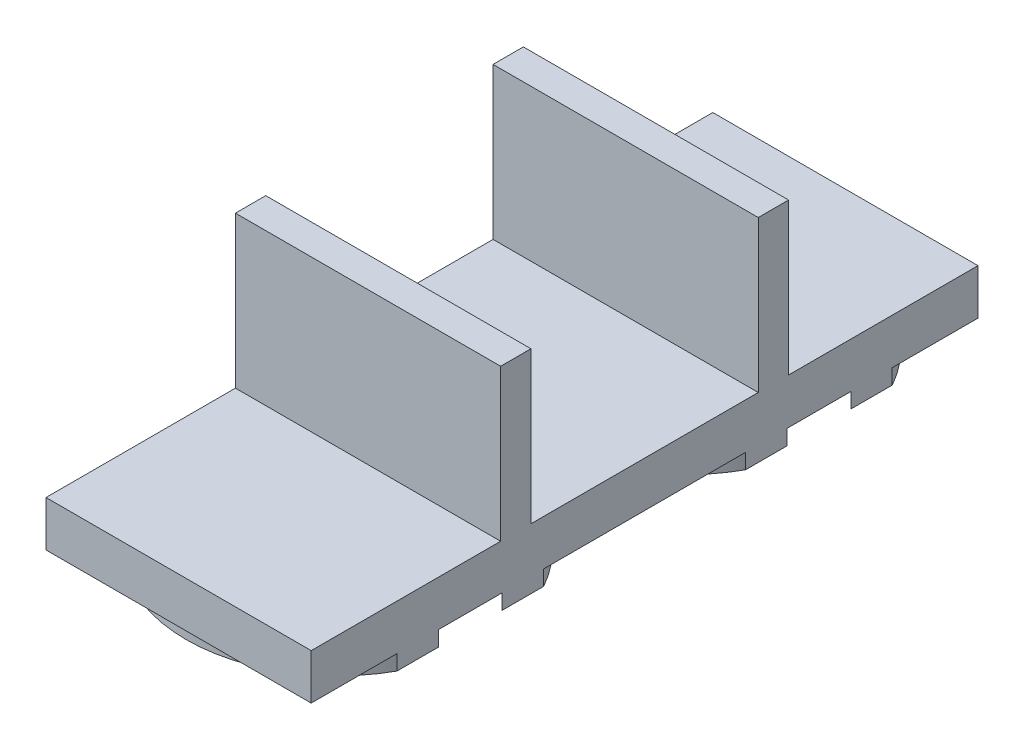
SolidWorks part; units mm, degrees
material "1060 合金"
ref_plane "前视" through (0, 0, 0) normal (0, 0, 1) x (1, 0, 0)
ref_plane "上视" through (0, 0, 0) normal (0, 1, 0) x (1, 0, 0)
ref_plane "右视" through (0, 0, 0) normal (1, 0, 0) x (0, 0, -1)
sketch "草图1" plane through (0, 0, 0) normal (1, 0, 0) x (0, 0, -1)
  line L0 (-44, 0) -> (44, 0)
  line L1 (44, 0) -> (44, 6)
  line L2 (44, 6) -> (19, 6)
  line L3 (19, 6) -> (19, 26)
  line L4 (19, 26) -> (15, 26)
  line L5 (15, 26) -> (15, 6)
  line L6 (15, 6) -> (-15, 6)
  line L7 (-15, 6) -> (-15, 26)
  line L8 (-15, 26) -> (-19, 26)
  line L9 (-19, 26) -> (-19, 6)
  line L10 (-19, 6) -> (-44, 6)
  line L11 (-44, 6) -> (-44, 0)
  line L12 (0, -8.8833) -> (0, 32.4515) construction
  dimension "D1" = 20
  dimension "D2" = 20
  dimension "D3" = 30
  dimension "D4" = 88
  dimension "D5" = 6
  dimension "D6" = 4
  dimension "D7" = 4
  dimension "D8" = 6
  dimension "D9" = 6
extrude "凸台-拉伸1" add sketch "草图1" along normal blind 35
sketch "草图2" plane through (0, 0, 0) normal (0, -1, 0) x (1, 0, 0)
  line L2 (17.5, 53.3428) -> (17.5, -48.7439) construction
  line L3 (48.3159, 0) -> (-15.7437, 0) construction
  line L5 (35, 44) -> (35, -44) construction
  line L6 (0, 44) -> (0, -44) construction
  line L7 (35, 32.6825) -> (35, -32.6825)
  line L8 (0, -32.6825) -> (0, 32.6825)
  circle A0 centre (17.5, -23) radius 18
  circle A1 centre (17.5, 23) radius 18
  circle A2 centre (17.5, 23) radius 20
  circle A3 centre (17.5, -23) radius 20
  line M1 (0, 44) -> (0, -44)
  line M3 (35, -44) -> (35, 44)
  dimension "D1" = 36
  dimension "D2" = 40
  dimension "D3" = 36
  dimension "D4" = 40
  dimension "D5" = 46
extrude "凸台-拉伸2" add sketch "草图2" along normal blind 2 contours A2 A1 M3 M1 | A2 L7 A1 M1 | A3 A0 M3 M1 | A3 A0 M1 M3
sketch "草图3" plane through (0, 0, 0) normal (0, -1, 0) x (1, 0, 0)
  circle A0 centre (17.5, 23) radius 2
  circle A1 centre (17.5, -23) radius 2
  dimension "D1" = 4
  dimension "D2" = 4
